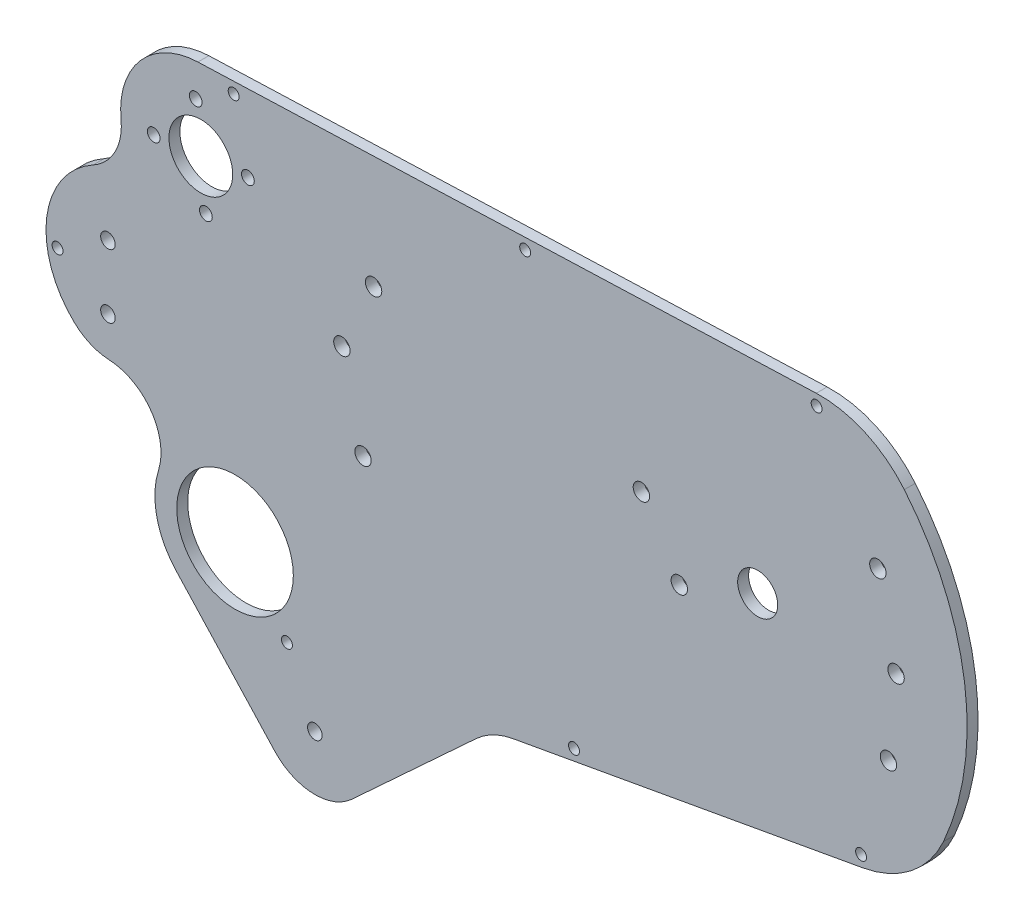
SolidWorks part; units mm, degrees
ref_plane "Front Plane" through (0, 0, 0) normal (0, 0, 1) x (1, 0, 0)
ref_plane "Top Plane" through (0, 0, 0) normal (0, 1, 0) x (1, 0, 0)
ref_plane "Right Plane" through (0, 0, 0) normal (1, 0, 0) x (0, 0, -1)
sketch "Sketch1" plane through (0, 0, 0) normal (0, 0, 1) x (1, 0, 0)
  line L0 (86.8854, -33.5) -> (-137.2004, -33.5) construction
  line L1 (-111.886, 49.4802) -> (83.0489, 41.2139) construction
  line L2 (-115.2069, 49.6211) -> (-101.035, -81.6153) construction
  line L3 (-97.8208, -80.7688) -> (92.1699, -30.731) construction
  line L4 (78.7977, 41.3942) -> (86.7407, -32.1609) construction
  line L5 (-108.121, -15.9971) -> (82.7692, 4.6166) construction
  line L6 (91, -33.5) -> (-88.5, -33.5) construction
  line L7 (-97.4673, 5.5) -> (-155.3054, 5.5) construction
  line L8 (-138.3, -14) -> (-155.3054, -14) construction
  line L9 (-138.3, 5.5) -> (-138.3, -33.5) construction
  line L10 (-155.3054, 5.5) -> (-155.3054, -33.5) construction
  line L11 (40.0178, 33.5) -> (40.0178, -33.5) construction
  line L12 (-101.0559, -81.4218) -> (-90.5433, -79.5278)
  line L13 (-91.5, 33.5) -> (88, 33.5) construction
  line L14 (-68.3, -21.5) -> (-107.0746, -25.6872) construction
  line L15 (-138.3, -5.25) -> (-81.5148, -93.5701) construction
  line L17 (-119.5948, -74.4106) -> (-92.5405, -103.7404)
  line L18 (-71.3446, -104.5958) -> (-37.2211, -73.1197)
  line L19 (-27.1401, -68.1042) -> (68.9251, -50.7959)
  line L20 (-117.3596, 49.3503) -> (56.0883, 55.6165)
  circle A0 centre (40.0178, 0) radius 5.5
  circle A1 centre (-112.8181, 27.5) radius 13 construction
  circle A2 centre (-103.4238, -59.4942) radius 13 construction
  arc A3 (-91.5, 33.5) -> (-88.5, -33.5) centre (-18.0922, 3.2198) ccw construction
  circle A4 centre (-68.3, -21.5) radius 2.25
  circle A6 centre (-138.3, -5.25) radius 2
  circle A7 centre (-138.3, -22.75) radius 2
  arc A8 (-142.3827, 10.6321) -> (-147.5429, -29.3643) centre (-130.3054, -11.2571) ccw
  arc A9 (-147.5429, -29.3643) -> (-137.2004, -33.5) centre (-137.2004, -18.5) ccw
  circle A10 centre (-112.8181, 27.5) radius 22
  arc A11 (68.9251, -50.7959) -> (91, -33.5) centre (63.6055, -21.2712) ccw
  circle A12 centre (-103.4238, -59.4942) radius 22
  arc A13 (91, -33.5) -> (80.2612, 44.7896) centre (22.6589, -2.9929) ccw
  arc A14 (91, -33.5) -> (88, 33.5) centre (22.6589, -2.9929) ccw construction
  arc A17 (-124.4228, -52.9336) -> (-137.9704, -33.4802) centre (-138.7403, -48.4604) ccw
  arc A18 (-142.3827, 10.6321) -> (-134.7058, 25.2795) centre (-149.6292, 23.7656) ccw
  circle A19 centre (-74.1, 1.7) radius 2.25
  circle A20 centre (-65.4, 20.2) radius 2.25
  circle A21 centre (8.1, 8.2) radius 2.25
  circle A23 centre (18.5, -8.7) radius 2.25
  circle A25 centre (78, -0.1) radius 2.25
  circle A26 centre (75.9, -21.8) radius 2.25
  circle A27 centre (73, 22.4) radius 2.25
  arc A28 (80.2612, 44.7896) -> (56.0883, 55.6165) centre (57.1714, 25.636) ccw
  circle A30 centre (-81.5148, -93.5701) radius 2
  circle A36 centre (-114.2138, 40.4249) radius 1.75
  circle A37 centre (-99.8933, 28.8957) radius 1.75
  circle A38 centre (-111.4224, 14.5751) radius 1.75
  circle A39 centre (-125.743, 26.1043) radius 1.75
  circle A40 centre (-104.8196, -46.5694) radius 1.75
  circle A41 centre (-90.499, -58.0985) radius 1.75
  circle A42 centre (-102.0281, -72.4191) radius 1.75
  circle A43 centre (-116.3487, -60.89) radius 1.75
  circle A44 centre (40.0178, 0) radius 35 construction
  circle A45 centre (40.0178, 0) radius 43
  circle A49 centre (-103.4238, -59.4942) radius 16
  circle A50 centre (-112.8181, 27.5) radius 16
  circle A51 centre (-112.8181, 27.5) radius 8.75
  circle A52 centre (-103.4238, -59.4942) radius 8.75
  arc A53 (91, -33.5) -> (88, 33.5) centre (22.6589, -2.9929) ccw construction
  arc A54 (-92.5405, -103.7404) -> (-71.3446, -104.5958) centre (-81.5148, -93.5701) ccw
  arc A55 (-27.1401, -68.1042) -> (-37.2211, -73.1197) centre (-23.5699, -87.9191) ccw
  circle A56 centre (-68.3, -21.5) radius 2.25 construction
  circle A57 centre (-74.1, 1.7) radius 2.25 construction
  circle A58 centre (-65.4, 20.2) radius 2.25 construction
  circle A59 centre (18.5, -8.7) radius 2.25 construction
  circle A60 centre (8.1, 8.2) radius 2.25 construction
  circle A61 centre (75.9, -21.8) radius 2.25 construction
  circle A62 centre (78, -0.1) radius 2.25 construction
  circle A63 centre (73, 22.4) radius 2.25 construction
  point P52 (82.7692, 4.6166)
  point P109 (-112.8181, 27.5)
  point P118 (-103.4238, -59.4942)
  dimension "D5" = 4
  dimension "D6" = 25
  dimension "D9" = 15
  dimension "D13" = 30
  dimension "D14" = 26
  dimension "D11" = 44
  dimension "D15" = 3.5
  dimension "D12" = 70
  dimension "D19" = 11
  dimension "D20" = 17.5
  dimension "D22" = 32
  dimension "D24" = 4
  dimension "D26" = 55
  dimension "D2" = 39
  dimension "D3" = 70
  dimension "D4" = 17.5
  dimension "D7" = 14
  dimension "D8" = 10
  dimension "D10" = 87.5
  dimension "D21" = 192
  dimension "D23" = 39
  dimension "D25" = 105
  dimension "D18" = 8
  dimension "D16" = 4
  dimension "D17" = 4
extrude "Boss-Extrude1" add sketch "Sketch1" along normal blind 3
sketch "Sketch2" plane through (0, 0, 3) normal (0, 0, 1) x (1, 0, 0)
  line L0 (68.3931, -47.8434) -> (-10.3905, -62.0381) construction
  line L1 (-138.3, -5.25) -> (-138.3, -22.75) construction
  line L2 (-10.3905, -62.0381) -> (-89.1742, -76.2328) construction
  line L7 (56.1966, 52.6184) -> (-113.5041, 46.4876)
  line L8 (56.1966, 52.6184) -> (-113.5041, 46.4876)
  line L9 (-103.8034, 46.8381) -> (-23.8034, 49.7282) construction
  line L10 (-23.8034, 49.7282) -> (56.1966, 52.6184) construction
  line L13 (-117.3897, -72.3766) -> (-90.3354, -101.7064)
  line L14 (-73.3786, -102.3907) -> (-39.2552, -70.9146)
  line L15 (-27.672, -65.1517) -> (68.3931, -47.8434)
  line L17 (-117.3897, -72.3766) -> (-90.3354, -101.7064) construction
  line L18 (-73.3786, -102.3907) -> (-39.2552, -70.9146) construction
  line L19 (-110.3186, -80.0424) -> (68.3931, -47.8434) construction
  circle A0 centre (-10.3905, -62.0381) radius 1.5
  circle A2 centre (-89.1742, -76.2328) radius 1.5
  arc A14 (77.9522, 42.8742) -> (56.1966, 52.6184) centre (57.1714, 25.636) ccw
  arc A15 (77.9522, 42.8742) -> (56.1966, 52.6184) centre (57.1714, 25.636) ccw
  arc A16 (68.3931, -47.8434) -> (88.2606, -32.2771) centre (63.6055, -21.2712) ccw
  arc A17 (-114.7845, -75.2008) -> (-103.8362, -78.8745) centre (-105.964, -67.0646) ccw construction
  circle A21 centre (68.3931, -47.8434) radius 1.5
  circle A23 centre (56.1966, 52.6184) radius 1.5
  circle A24 centre (-23.8034, 49.7282) radius 1.5
  circle A27 centre (-103.8034, 46.8381) radius 1.5
  arc A28 (-113.5041, 46.4876) -> (-131.7211, 25.5823) centre (-112.8181, 27.5) ccw
  arc A29 (-140.9335, 8.0053) -> (-131.7211, 25.5823) centre (-149.6292, 23.7656) ccw
  arc A30 (-140.9335, 8.0053) -> (-145.4744, -27.1914) centre (-130.3054, -11.2571) ccw
  arc A31 (-145.4744, -27.1914) -> (-137.8164, -30.4842) centre (-137.2004, -18.5) ccw
  arc A32 (-121.5593, -53.8282) -> (-137.8164, -30.4842) centre (-138.7403, -48.4604) ccw
  arc A33 (-121.5593, -53.8282) -> (-117.3897, -72.3766) centre (-103.4238, -59.4942) ccw
  arc A34 (-90.3354, -101.7064) -> (-73.3786, -102.3907) centre (-81.5148, -93.5701) ccw
  arc A35 (-27.672, -65.1517) -> (-39.2552, -70.9146) centre (-23.5699, -87.9191) ccw
  arc A36 (88.2606, -32.2771) -> (77.9522, 42.8742) centre (22.6589, -2.9929) ccw
  arc A37 (-113.5041, 46.4876) -> (-131.7211, 25.5823) centre (-112.8181, 27.5) ccw construction
  arc A38 (-140.9335, 8.0053) -> (-131.7211, 25.5823) centre (-149.6292, 23.7656) ccw construction
  arc A39 (-140.9335, 8.0053) -> (-145.4744, -27.1914) centre (-130.3054, -11.2571) ccw construction
  arc A40 (-145.4744, -27.1914) -> (-137.8164, -30.4842) centre (-137.2004, -18.5) ccw construction
  arc A41 (-121.5593, -53.8282) -> (-137.8164, -30.4842) centre (-138.7403, -48.4604) ccw construction
  arc A42 (-121.5593, -53.8282) -> (-117.3897, -72.3766) centre (-103.4238, -59.4942) ccw construction
  arc A43 (-90.3354, -101.7064) -> (-73.3786, -102.3907) centre (-81.5148, -93.5701) ccw construction
  arc A44 (-27.672, -65.1517) -> (-39.2552, -70.9146) centre (-23.5699, -87.9191) ccw construction
  arc A45 (88.2606, -32.2771) -> (77.9522, 42.8742) centre (22.6589, -2.9929) ccw construction
  circle A47 centre (-152.1337, -14) radius 1.5
  arc A51 (68.3931, -47.8434) -> (88.2606, -32.2771) centre (63.6055, -21.2712) ccw
  point P2 (-138.3, -14)
  point P3 (64.9505, 52.6314)
  point P6 (-95.0495, 54.7353)
  point P8 (-95.0495, 47.1543)
  dimension "D4" = 3
  dimension "D2" = 80
  dimension "D1" = 3
extrude "Cut-Extrude1" cut sketch "Sketch2" against normal through all
